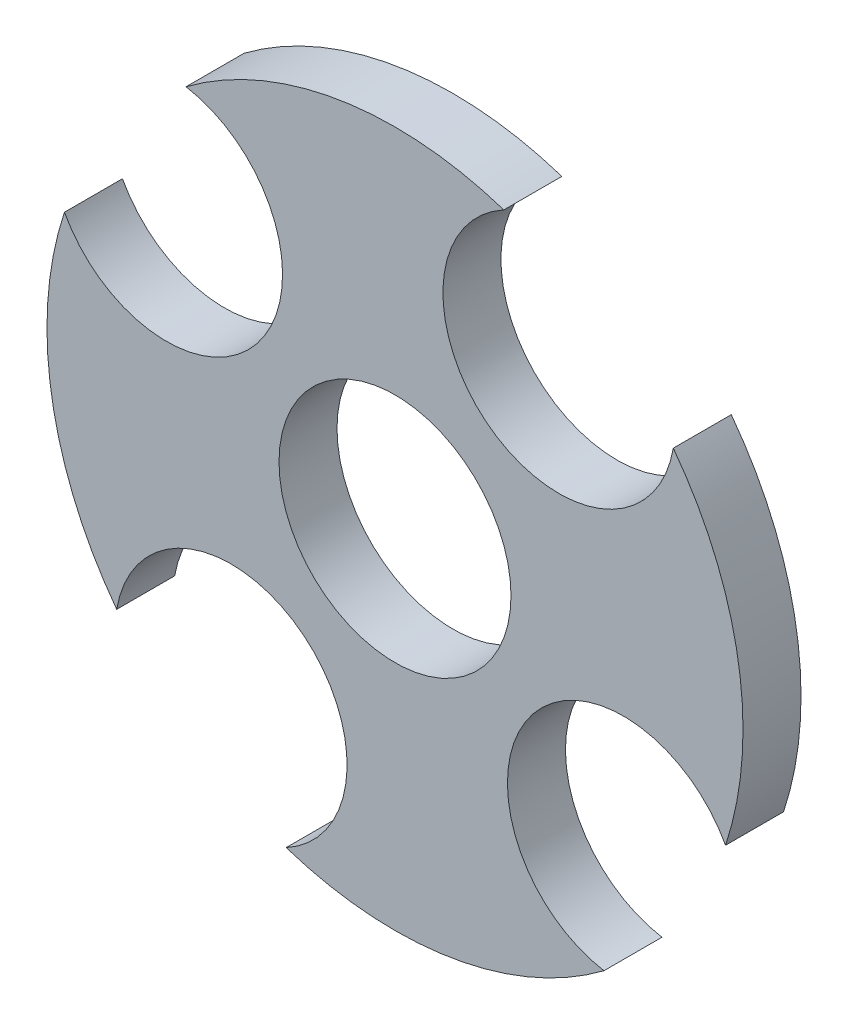
SolidWorks part; units mm, degrees
ref_plane "Front Plane" through (0, 0, 0) normal (0, 0, 1) x (1, 0, 0)
ref_plane "Top Plane" through (0, 0, 0) normal (0, 1, 0) x (1, 0, 0)
ref_plane "Right Plane" through (0, 0, 0) normal (1, 0, 0) x (0, 0, -1)
sketch "Sketch1" plane through (0, 0, 0) normal (0, 0, 1) x (1, 0, 0)
  arc A0 (-18.0942, 5.9584) -> (-15.2336, -11.4385) centre (0, 0) ccw
  circle A1 centre (0, 0) radius 6.35
  arc A2 (-18.0942, 5.9584) -> (-11.4385, 15.2336) centre (-12.5059, 8.974) ccw
  arc A3 (5.9584, 18.0942) -> (15.2336, 11.4385) centre (8.974, 12.5059) ccw
  arc A4 (18.0942, -5.9584) -> (11.4385, -15.2336) centre (12.5059, -8.974) ccw
  arc A5 (-5.9584, -18.0942) -> (-15.2336, -11.4385) centre (-8.974, -12.5059) ccw
  arc A6 (18.0942, -5.9584) -> (15.2336, 11.4385) centre (0, 0) ccw
  arc A7 (5.9584, 18.0942) -> (-11.4385, 15.2336) centre (0, 0) ccw
  arc A8 (-5.9584, -18.0942) -> (11.4385, -15.2336) centre (0, 0) ccw
  dimension "D1" = 38.1
  dimension "D3" = 12.7
  dimension "D4" = 12.7
  dimension "D6" = 12.7
  dimension "D7" = 12.7
  dimension "D8" = 12.7
extrude "Boss-Extrude1" add sketch "Sketch1" along normal blind 3.175
